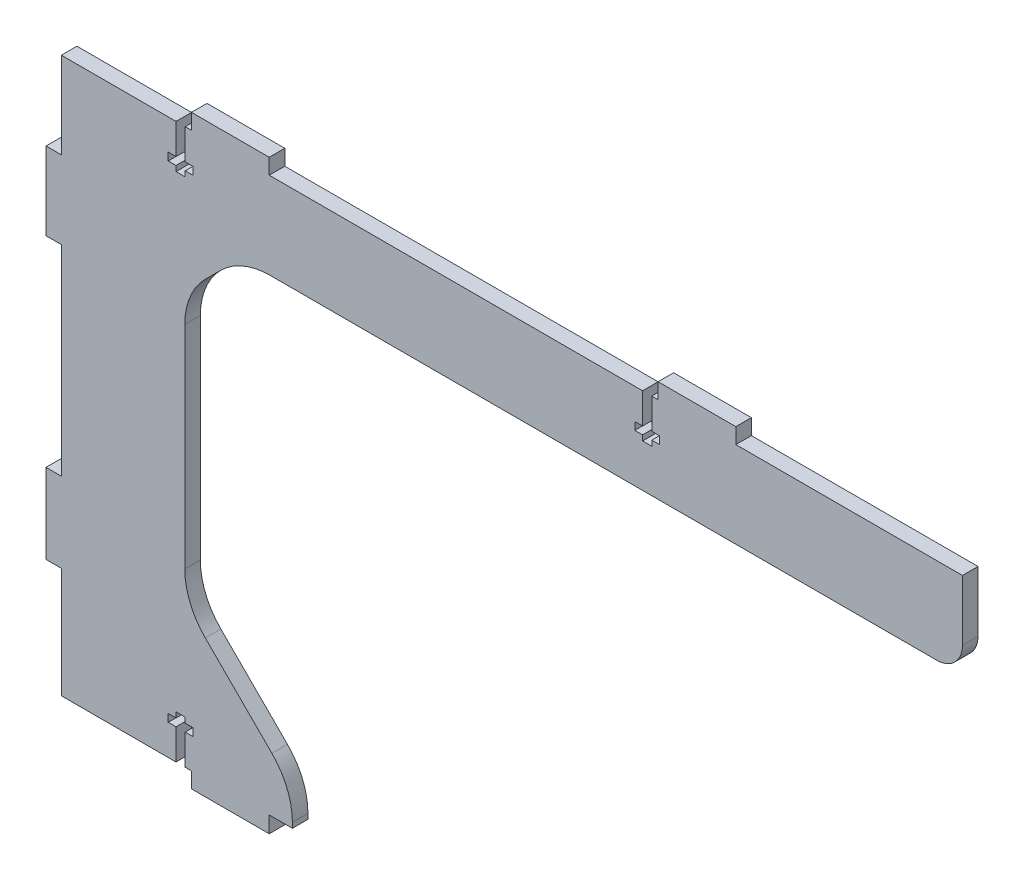
SolidWorks part; units mm, degrees
ref_plane "Front Plane" through (0, 0, 0) normal (0, 0, 1) x (1, 0, 0)
ref_plane "Top Plane" through (0, 0, 0) normal (0, 1, 0) x (1, 0, 0)
ref_plane "Right Plane" through (0, 0, 0) normal (1, 0, 0) x (0, 0, -1)
sketch "Sketch1" plane through (0, 0, 0) normal (0, 0, 1) x (1, 0, 0)
  line L0 (-114.3768, 88.6671) -> (-139.7768, 88.6671)
  line L1 (-139.7768, 88.6671) -> (-139.7768, 93.7471)
  line L2 (-139.7768, 93.7471) -> (-141.8223, 93.7471)
  line L3 (-114.102, 246.7718) -> (103.6377, 246.7718)
  line L4 (-106.8106, 274.9615) -> (7.5777, 274.9615)
  line L5 (112.0508, 274.9615) -> (112.0508, 255.185)
  line L6 (-144.8223, 93.7471) -> (-182.2695, 93.7471)
  line L7 (-182.2695, 93.7471) -> (-182.2695, 129.8108)
  line L8 (-182.2695, 129.8108) -> (-187.2865, 129.8108)
  line L9 (-187.2865, 129.8108) -> (-187.2865, 155.8715)
  line L10 (-187.2865, 155.8715) -> (-182.2695, 155.8715)
  line L11 (-182.2695, 93.7471) -> (-182.2695, 274.9615) construction
  line L12 (-182.2695, 184.3543) -> (-156.2826, 184.3543) construction
  line L13 (-182.2695, 274.9615) -> (-182.2695, 246.7718)
  line L14 (-144.8223, 274.9615) -> (-182.2695, 274.9615)
  line L15 (-114.3768, 280.0415) -> (-139.7768, 280.0415)
  line L16 (-187.2865, 246.7718) -> (-187.2865, 221.3718)
  line L17 (-187.2865, 221.3718) -> (-182.2695, 221.3718)
  line L18 (-182.2695, 221.3718) -> (-182.2695, 212.837)
  line L19 (-143.3223, 107.9471) -> (-143.3223, 105.6208) construction
  line L20 (-144.8223, 107.9471) -> (-141.8223, 107.9471) construction
  line L21 (-141.8223, 107.9471) -> (-141.8223, 106.213)
  line L22 (-139.7768, 274.9615) -> (-141.8223, 274.9615)
  line L23 (-139.7768, 280.0415) -> (-139.7768, 274.9615)
  line L24 (-114.3768, 88.9386) -> (-114.3768, 93.9938)
  line L26 (-114.3768, 93.9938) -> (-106.8106, 93.9938)
  line L27 (-106.8106, 93.9938) -> (-106.8106, 95.7075)
  line L28 (-106.8106, 274.9615) -> (-114.3768, 274.9615)
  line L29 (-114.3768, 274.9615) -> (-114.3768, 280.0415)
  line L30 (-113.5061, 111.872) -> (-135.2536, 133.6194)
  line L31 (-141.9492, 149.7839) -> (-141.9492, 218.9246)
  line L32 (-130.2665, 240.0762) -> (-135.2536, 235.0891)
  line L33 (12.6232, 280.0415) -> (12.6232, 274.9615)
  line L34 (-144.8223, 260.7615) -> (-141.8223, 260.7615) construction
  line L35 (-143.3223, 260.7615) -> (-143.3223, 263.0877) construction
  line L36 (-144.8223, 274.9615) -> (-144.8223, 264.9955)
  line L37 (-144.8223, 262.4955) -> (-147.3623, 262.4955)
  line L38 (-147.3623, 262.4955) -> (-147.3623, 264.9955)
  line L39 (-141.8223, 264.9955) -> (-141.8223, 274.9615)
  line L40 (-147.3623, 264.9955) -> (-144.8223, 264.9955)
  line L41 (-144.8223, 262.4955) -> (-144.8223, 260.7615)
  line L42 (-141.8223, 262.4955) -> (-139.2823, 262.4955)
  line L43 (-139.2823, 262.4955) -> (-139.2823, 264.9955)
  line L44 (-139.2823, 264.9955) -> (-141.8223, 264.9955)
  line L45 (-144.8223, 260.7615) -> (-141.8223, 260.7615)
  line L46 (-141.8223, 260.7615) -> (-141.8223, 262.4955)
  line L47 (-144.8223, 107.9471) -> (-141.8223, 107.9471)
  line L48 (-139.2823, 103.713) -> (-141.8223, 103.713)
  line L49 (-139.2823, 106.213) -> (-139.2823, 103.713)
  line L50 (-141.8223, 106.213) -> (-139.2823, 106.213)
  line L51 (-144.8223, 106.213) -> (-144.8223, 107.9471)
  line L52 (-147.3623, 103.713) -> (-144.8223, 103.713)
  line L53 (-141.8223, 103.713) -> (-141.8223, 93.7471)
  line L54 (-147.3623, 106.213) -> (-147.3623, 103.713)
  line L55 (-144.8223, 106.213) -> (-147.3623, 106.213)
  line L56 (-144.8223, 93.7471) -> (-144.8223, 103.713)
  line L57 (38.0232, 280.0415) -> (12.6232, 280.0415)
  line L58 (38.0232, 274.9615) -> (38.0232, 280.0415)
  line L59 (7.5777, 274.9615) -> (7.5777, 264.9955)
  line L60 (10.5777, 264.9955) -> (10.5777, 274.9615)
  line L61 (13.1177, 264.9955) -> (10.5777, 264.9955)
  line L62 (13.1177, 262.4955) -> (13.1177, 264.9955)
  line L63 (5.0377, 264.9955) -> (7.5777, 264.9955)
  line L64 (5.0377, 262.4955) -> (5.0377, 264.9955)
  line L65 (7.5777, 262.4955) -> (5.0377, 262.4955)
  line L66 (7.5777, 262.4955) -> (7.5777, 260.7615)
  line L67 (7.5777, 260.7615) -> (10.5777, 260.7615)
  line L68 (10.5777, 260.7615) -> (10.5777, 262.4955)
  line L69 (10.5777, 262.4955) -> (13.1177, 262.4955)
  line L70 (38.0232, 274.9615) -> (112.0508, 274.9615)
  line L71 (10.5777, 274.9615) -> (12.6232, 274.9615)
  line L72 (-182.2695, 155.8715) -> (-182.2695, 212.837)
  line L73 (-114.3768, 88.6671) -> (-114.3768, 88.9386)
  line L74 (-182.2695, 246.7718) -> (-187.2865, 246.7718)
  arc A0 (-113.5061, 111.872) -> (-106.8106, 95.7075) centre (-129.6706, 95.7075) cw
  arc A1 (-135.2536, 133.6194) -> (-141.9492, 149.7839) centre (-119.0892, 149.7839) cw
  arc A2 (-135.2536, 235.0891) -> (-141.9492, 218.9246) centre (-119.0892, 218.9246) ccw
  arc A3 (-114.102, 246.7718) -> (-130.2665, 240.0762) centre (-114.102, 223.9118) ccw
  arc A4 (103.6377, 246.7718) -> (112.0508, 255.185) centre (103.6377, 255.185) ccw
  point P42 (-141.9492, 184.3543)
  point P44 (-106.8106, 105.1764)
  point P47 (-141.9492, 140.315)
  point P50 (-141.9492, 228.3936)
  point P53 (-106.8106, 263.5321)
  point P79 (112.0508, 246.7718)
  dimension "D1" = 22.86
  dimension "D4" = 22.86
  dimension "D2" = 254
  dimension "D6" = 25.4
  dimension "D5" = 2
extrude "Boss-Extrude1" add sketch "Sketch1" along normal blind 5.08 contours L7 L8 L9 L10 L72 L18 L17 L16 L74 L13 L14 L36 L40 L38 L37 L41 L45 L46 L42 L43 L44 L39 L22 L23 L15 L29 L28 L4 L59 L63 L64 L65 L66 L67 L68 L69 L62 L61 L60 L71 L33 L57 L58 L70 L5 A4 L3 A3 L32 A2 L31 A1 L30 A0 L27 L26 L24 L73 L0 L1 L2 L53 L48 L49 L50 L21 L47 L51 L55 L54 L52 L56 L6
